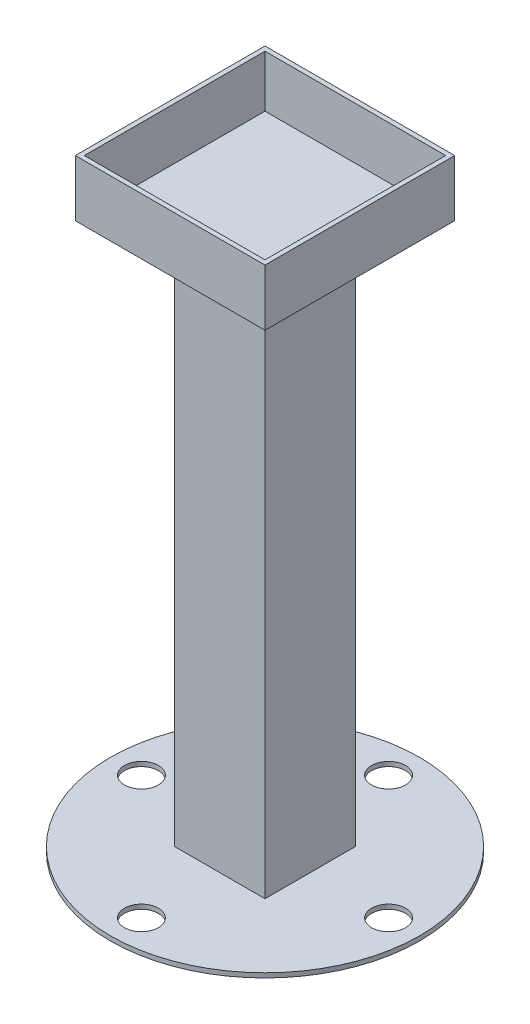
SolidWorks part; units mm, degrees
ref_plane "Front Plane" through (0, 0, 0) normal (0, 0, 1) x (1, 0, 0)
ref_plane "Top Plane" through (0, 0, 0) normal (0, 1, 0) x (1, 0, 0)
ref_plane "Right Plane" through (0, 0, 0) normal (1, 0, 0) x (0, 0, -1)
sketch "Sketch1" plane through (0, 0, 0) normal (0, 1, 0) x (1, 0, 0)
  circle A0 centre (0, 0) radius 86.9315
extrude "Boss-Extrude1" add sketch "Sketch1" along normal blind 2.54
sketch "Sketch2" plane through (0, 2.54, 0) normal (0, 1, 0) x (1, 0, 0)
  line L1 (-25.4, 25.4) -> (25.4, 25.4)
  line L2 (-25.4, 25.4) -> (-25.4, -25.4)
  line L3 (-25.4, -25.4) -> (25.4, -25.4)
  line L4 (25.4, 25.4) -> (25.4, -25.4)
  line L5 (-25.4, 25.4) -> (25.4, -25.4) construction
  line L6 (-25.4, -25.4) -> (25.4, 25.4) construction
  point P0 (0, 0)
extrude "Boss-Extrude2" add sketch "Sketch2" along normal blind 304.8
sketch "Sketch3" plane through (0, 307.34, 0) normal (0, 1, 0) x (1, 0, 0)
  line L0 (-53.34, 53.34) -> (-53.34, -53.34)
  line L5 (-53.34, -53.34) -> (53.34, -53.34)
  line L6 (53.34, 53.34) -> (53.34, -53.34)
  line L7 (-53.34, 53.34) -> (53.34, 53.34)
  point P1 (0, 0)
extrude "Boss-Extrude4" add sketch "Sketch3" along normal blind 31.75
sketch "Sketch4" plane through (0, 339.09, 0) normal (0, 1, 0) x (1, 0, 0)
  line L1 (-50.8, 50.8) -> (50.8, 50.8)
  line L2 (-50.8, 50.8) -> (-50.8, -50.8)
  line L3 (-50.8, -50.8) -> (50.8, -50.8)
  line L4 (50.8, 50.8) -> (50.8, -50.8)
  line L5 (-50.8, 50.8) -> (50.8, -50.8) construction
  line L6 (-50.8, -50.8) -> (50.8, 50.8) construction
  point P0 (0, 0)
extrude "Cut-Extrude1" cut sketch "Sketch4" against normal blind 29.21
sketch "Sketch5" plane through (0, 2.54, 0) normal (0, 1, 0) x (1, 0, 0)
  line L2 (-86.9315, -12.7) -> (-12.7, -12.7)
  line L3 (-86.9315, 12.7) -> (-12.7, 12.7)
  line L4 (-12.7, 86.9315) -> (-12.7, 12.7)
  line L5 (12.7, 86.9315) -> (12.7, 12.7)
  line L7 (12.7, 12.7) -> (86.9315, 12.7)
  line L11 (-12.7, -12.7) -> (-12.7, -86.9315)
  line L13 (12.7, -12.7) -> (12.7, -86.9315)
  line L15 (12.7, -12.7) -> (86.9315, -12.7)
sketch "Sketch6" plane through (0, 2.54, 0) normal (0, 1, 0) x (1, 0, 0)
  line L8 (0, 86.9315) -> (0, 52.07) construction
  line L9 (-86.9315, 0) -> (-52.07, 0) construction
  line L10 (0, -52.07) -> (0, -86.9315) construction
  line L15 (52.07, 0) -> (86.9315, 0) construction
  circle A10 centre (0, 69.5007) radius 9.525
  circle A11 centre (69.5007, 0) radius 9.525
  circle A12 centre (0, -69.5007) radius 9.525
  circle A13 centre (-69.5007, 0) radius 9.525
  point P0 (0, 0)
extrude "Cut-Extrude3" cut sketch "Sketch6" against normal blind 29.21
